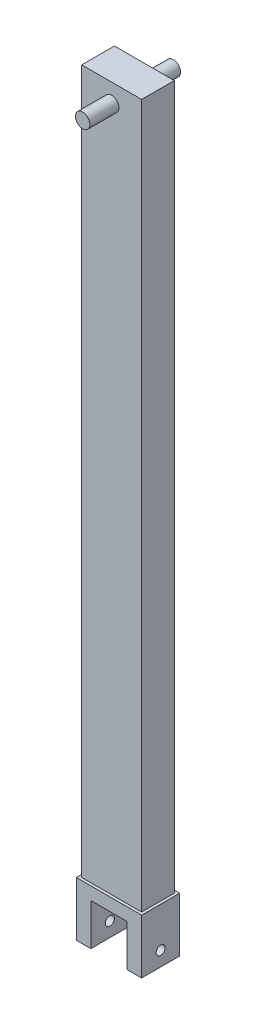
SolidWorks part; units mm, degrees
ref_plane "Front Plane" through (0, 0, 0) normal (0, 0, 1) x (1, 0, 0)
ref_plane "Top Plane" through (0, 0, 0) normal (0, 1, 0) x (1, 0, 0)
ref_plane "Right Plane" through (0, 0, 0) normal (1, 0, 0) x (0, 0, -1)
sketch "Sketch1" plane through (0, 0, 0) normal (0, 1, 0) x (1, 0, 0)
  line L1 (-16.5, 9) -> (16.5, 9)
  line L2 (-16.5, 9) -> (-16.5, -9)
  line L3 (-16.5, -9) -> (16.5, -9)
  line L4 (16.5, 9) -> (16.5, -9)
  line L5 (-16.5, 9) -> (16.5, -9) construction
  line L6 (-16.5, -9) -> (16.5, 9) construction
  point P0 (0, 0)
extrude "Boss-Extrude1" add sketch "Sketch1" along normal blind 388
ref_plane "Plane1" through (0, 0, 0) normal (0, 0, 1) x (1, 0, 0)
sketch "Sketch3" plane through (0, 0, 0) normal (0, 0, 1) x (1, 0, 0)
  line L0 (-16.5, 388) -> (16.5, 388) construction
  circle A0 centre (0, 377.75) radius 4
  dimension "D1" = 10.25
extrude "Boss-Extrude2" add sketch "Sketch3" along normal mid plane 50
sketch "Sketch4" plane through (0, 0, 0) normal (0, -1, 0) x (1, 0, 0)
  line L1 (-18, 10.5) -> (18, 10.5)
  line L2 (-18, 10.5) -> (-18, -10.5)
  line L3 (-18, -10.5) -> (18, -10.5)
  line L4 (18, 10.5) -> (18, -10.5)
  line L5 (-18, 10.5) -> (18, -10.5) construction
  line L6 (-18, -10.5) -> (18, 10.5) construction
  point P0 (0, 0)
extrude "Boss-Extrude3" add sketch "Sketch4" along normal blind 30
sketch "Sketch5" plane through (0, 0, 10.5) normal (0, 0, 1) x (1, 0, 0)
  line L0 (18, -30) -> (-18, -30) construction
  line L1 (-10, -52.9912) -> (10, -52.9912)
  line L2 (-10, -52.9912) -> (-10, -7.0088)
  line L3 (-10, -7.0088) -> (10, -7.0088)
  line L4 (10, -52.9912) -> (10, -7.0088)
  line L5 (-10, -52.9912) -> (10, -7.0088) construction
  line L6 (-10, -7.0088) -> (10, -52.9912) construction
  point P0 (0, -30)
extrude "Cut-Extrude1" cut sketch "Sketch5" against normal through all
sketch "Sketch6" plane through (18, 0, 0) normal (1, 0, 0) x (0, 0, -1)
  line L0 (0, 18.15) -> (0, -18.15) construction
  line L1 (10.5, -30) -> (-10.5, -30) construction
  circle A0 centre (0, -22) radius 2.5
  dimension "D1" = 8
extrude "Cut-Extrude2" cut sketch "Sketch6" against normal through all
